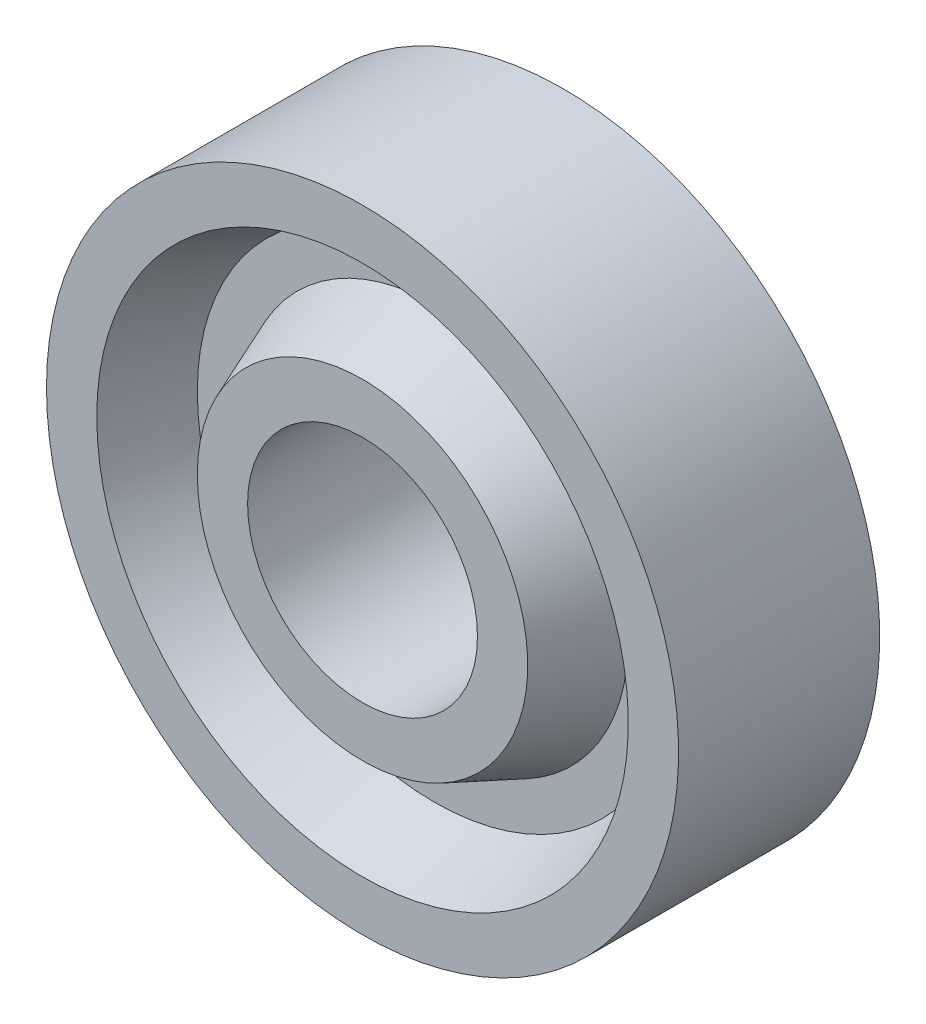
SolidWorks part; units mm, degrees
ref_plane "Front Plane" through (0, 0, 0) normal (0, 0, 1) x (1, 0, 0)
ref_plane "Top Plane" through (0, 0, 0) normal (0, 1, 0) x (1, 0, 0)
ref_plane "Right Plane" through (0, 0, 0) normal (1, 0, 0) x (0, 0, -1)
sketch "Sketch1" plane through (0, 0, 0) normal (0, 1, 0) x (1, 0, 0)
  line L0 (0, 28.9111) -> (0, -36.6207) construction
  line L2 (5.75, 3.5) -> (6.75, 1)
  line L3 (6.75, 1) -> (8.25, 1)
  line L4 (8.25, 1) -> (9.25, 3.5)
  line L6 (11, 3.5) -> (11, -3.5)
  line L8 (9.25, -3.5) -> (8.25, -1)
  line L9 (8.25, -1) -> (6.75, -1)
  line L10 (6.75, -1) -> (5.75, -3.5)
  line L12 (4, -3.5) -> (4, 3.5)
  line L13 (0, 0) -> (4, 0) construction
  line L14 (6.75, -1) -> (6.75, 1) construction
  line L15 (8.25, -1) -> (8.25, 1) construction
  line L16 (4, 3.5) -> (5.75, 3.5)
  line L17 (9.25, 3.5) -> (11, 3.5)
  line L18 (9.25, -3.5) -> (11, -3.5)
  line L19 (4, -3.5) -> (5.75, -3.5)
  line L20 (5.75, -3.5) -> (9.25, -3.5) construction
  line L21 (5.75, 3.5) -> (9.25, 3.5) construction
  line L22 (5.75, -3.5) -> (5.75, 3.5) construction
  line L23 (9.25, -3.5) -> (9.25, 3.5) construction
  dimension "D1" = 4
  dimension "D2" = 11
  dimension "D3" = 3.5
  dimension "D5" = 2.5
  dimension "D6" = 7
  dimension "D7" = 1.5
revolve "Revolve1" add sketch "Sketch1" angle 360 about L0
